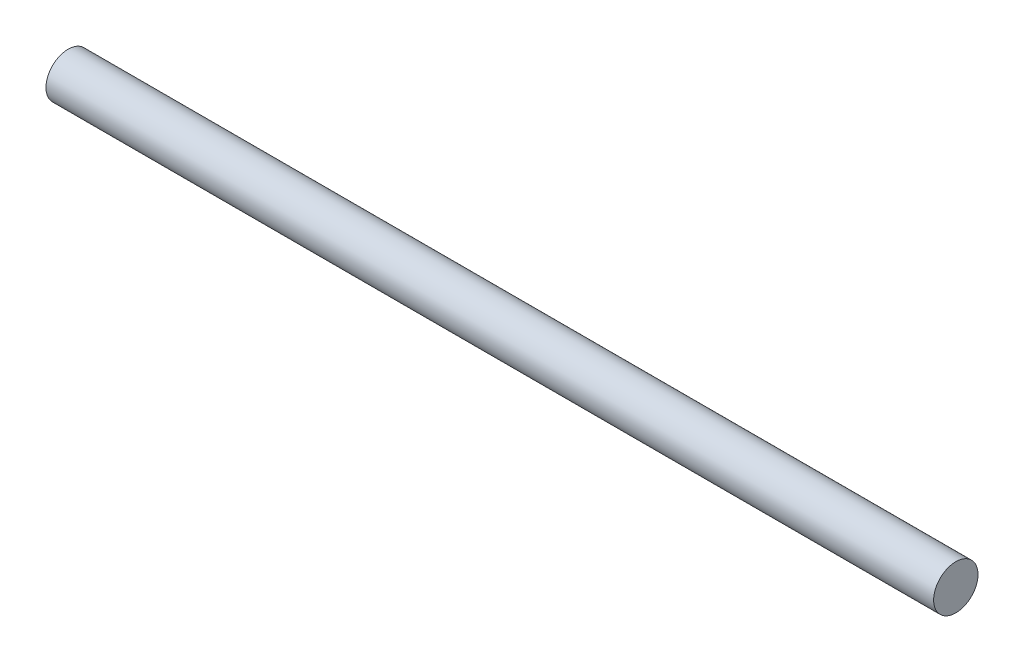
SolidWorks part; units mm, degrees
ref_plane "Front Plane" through (0, 0, 0) normal (0, 0, 1) x (1, 0, 0)
ref_plane "Top Plane" through (0, 0, 0) normal (0, 1, 0) x (1, 0, 0)
ref_plane "Right Plane" through (0, 0, 0) normal (1, 0, 0) x (0, 0, -1)
sketch "Sketch1" plane through (0, 0, 0) normal (1, 0, 0) x (0, 0, -1)
  circle A0 centre (0, 0) radius 2.5
  dimension "D1" = 5
extrude "Boss-Extrude1" add sketch "Sketch1" along normal blind 100
